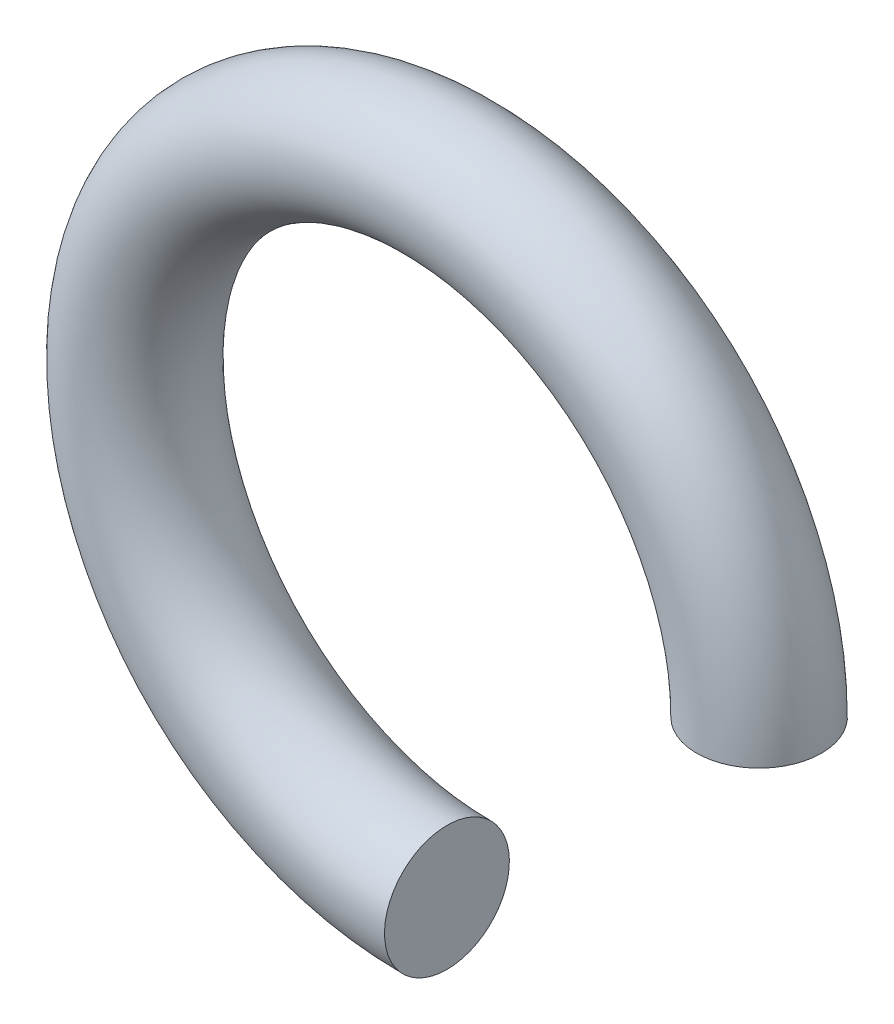
SolidWorks part; units mm, degrees
ref_plane "Front Plane" through (0, 0, 0) normal (0, 0, 1) x (1, 0, 0)
ref_plane "Top Plane" through (0, 0, 0) normal (0, 1, 0) x (1, 0, 0)
ref_plane "Right Plane" through (0, 0, 0) normal (1, 0, 0) x (0, 0, -1)
ref_plane "plane:profile" through (0, 0, 0) normal (0, -1, 0) x (1, 0, 0)
sketch "sketch:profile" plane through (0, 0, 0) normal (0, -1, 0) x (1, 0, 0)
  line L0 (0, -15) -> (0, 15) construction
  circle A0 centre (20, 0) radius 4
revolve "feature:torus" add sketch "sketch:profile" angle 270 about L0
